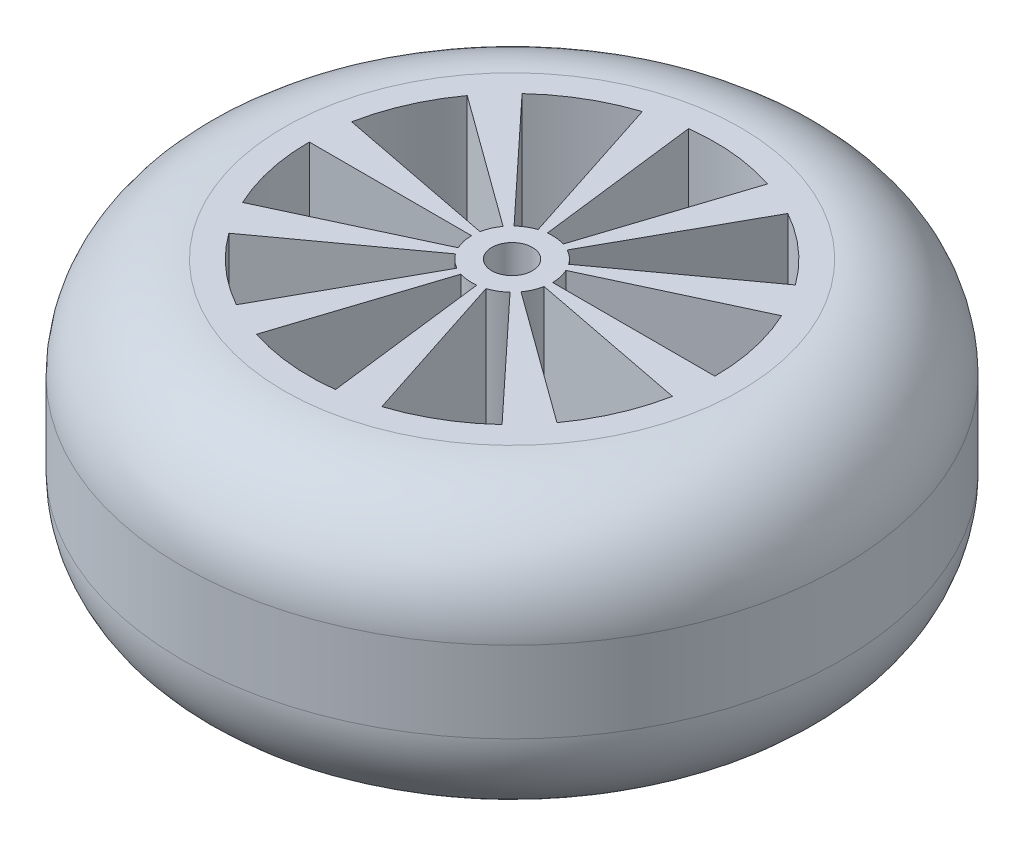
SolidWorks part; units mm, degrees
ref_plane "Front Plane" through (0, 0, 0) normal (0, 0, 1) x (1, 0, 0)
ref_plane "Top Plane" through (0, 0, 0) normal (0, 1, 0) x (1, 0, 0)
ref_plane "Right Plane" through (0, 0, 0) normal (1, 0, 0) x (0, 0, -1)
sketch "Sketch1" plane through (0, 0, 0) normal (0, 1, 0) x (1, 0, 0)
  circle A0 centre (0, 0) radius 32.5
  circle A1 centre (0, 0) radius 2
  dimension "D1" = 65
  dimension "D2" = 4
extrude "Boss-Extrude1" add sketch "Sketch1" along normal blind 28
fillet "Fillet1" radius 10 2 edges at (0, 0, 32.5) (0, 28, 32.5)
sketch "Sketch2" plane through (0, 28, 0) normal (0, 1, 0) x (1, 0, 0)
  line L0 (-20, 0) -> (20, 0)
  line L1 (16.1803, 11.7557) -> (-16.1803, -11.7557)
  line L2 (-6.1803, 19.0211) -> (6.1803, -19.0211)
  line L3 (-16.1803, 11.7557) -> (16.1803, -11.7557)
  line L4 (-6.1803, -19.0211) -> (6.1803, 19.0211)
  line L5 (18.1262, 8.4524) -> (-18.1262, -8.4524)
  line L6 (19.6325, -3.8162) -> (-19.6325, 3.8162)
  line L7 (13.64, -14.6271) -> (-13.64, 14.6271)
  line L8 (2.4374, -19.8509) -> (-2.4374, 19.8509)
  line L9 (-9.6962, -17.4924) -> (9.6962, 17.4924)
  circle A0 centre (0, 0) radius 20
  circle A1 centre (0, 0) radius 1.9821
  circle A2 centre (0, 0) radius 4
  dimension "D1" = 36
  dimension "D2" = 36
  dimension "D3" = 36
  dimension "D4" = 36
  dimension "D5" = 25
  dimension "D6" = 36
  dimension "D7" = 36
  dimension "D8" = 36
  dimension "D9" = 36
extrude "Cut-Extrude2" cut sketch "Sketch2" against normal blind 28 contours A2 L2 A0 L7 | A2 L4 A0 L8 | A2 L1 A0 L9 | A2 L0 A0 L5 | A2 L3 A0 L6 | A2 L2 A0 L7 | A2 L4 A0 L8 | A2 L1 A0 L9 | A2 L0 A0 L5 | A2 L3 A0 L6
